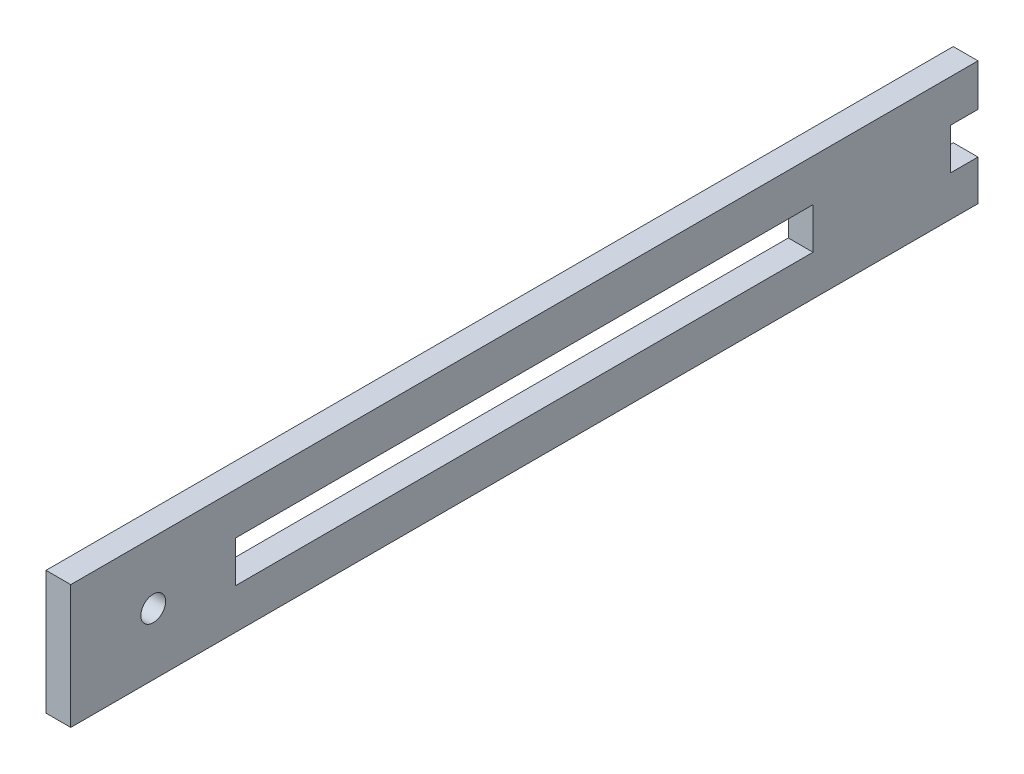
SolidWorks part; units mm, degrees
ref_plane "Front Plane" through (0, 0, 0) normal (0, 0, 1) x (1, 0, 0)
ref_plane "Top Plane" through (0, 0, 0) normal (0, 1, 0) x (1, 0, 0)
ref_plane "Right Plane" through (0, 0, 0) normal (1, 0, 0) x (0, 0, -1)
sketch "Sketch1" plane through (0, 0, 0) normal (1, 0, 0) x (0, 0, -1)
  line L1 (55, -7.5) -> (-55, -7.5)
  line L2 (55, -7.5) -> (55, 7.5)
  line L3 (55, 7.5) -> (-55, 7.5)
  line L4 (-55, -7.5) -> (-55, 7.5)
  line L5 (55, -7.5) -> (-55, 7.5) construction
  line L6 (55, 7.5) -> (-55, -7.5) construction
  line L7 (35, -2.6015) -> (-35, -2.6015)
  line L8 (35, -2.6015) -> (35, 2.3985)
  line L9 (35, 2.3985) -> (-35, 2.3985)
  line L10 (-35, -2.6015) -> (-35, 2.3985)
  line L11 (35, -2.6015) -> (-35, 2.3985) construction
  line L12 (35, 2.3985) -> (-35, -2.6015) construction
  point P0 (0, 0)
  point P6 (0, -0.1015)
  dimension "D1" = 15
  dimension "D2" = 110
  dimension "D3" = 5
  dimension "D4" = 20
  dimension "D5" = 70
  dimension "D6" = 5.1015
extrude "Boss-Extrude1" add sketch "Sketch1" along normal blind 3
sketch "Sketch2" plane through (3, 0, 0) normal (1, 0, 0) x (0, 0, -1)
  line L0 (-55, 7.5) -> (-55, -7.5) construction
  line L1 (55, 7.5) -> (-55, 7.5) construction
  line L2 (55, 2.3985) -> (51.6762, 2.3985)
  line L3 (55, -7.5) -> (55, 7.5) construction
  line L4 (51.6762, 2.3985) -> (51.6762, -2.6015)
  line L5 (51.6762, -2.6015) -> (55, -2.6015)
  line L6 (55, -2.6015) -> (55, 2.3985)
  circle A0 centre (-45, 0) radius 1.5
  dimension "D1" = 3
  dimension "D2" = 10
  dimension "D3" = 7.5
extrude "Cut-Extrude1" cut sketch "Sketch2" against normal through all
